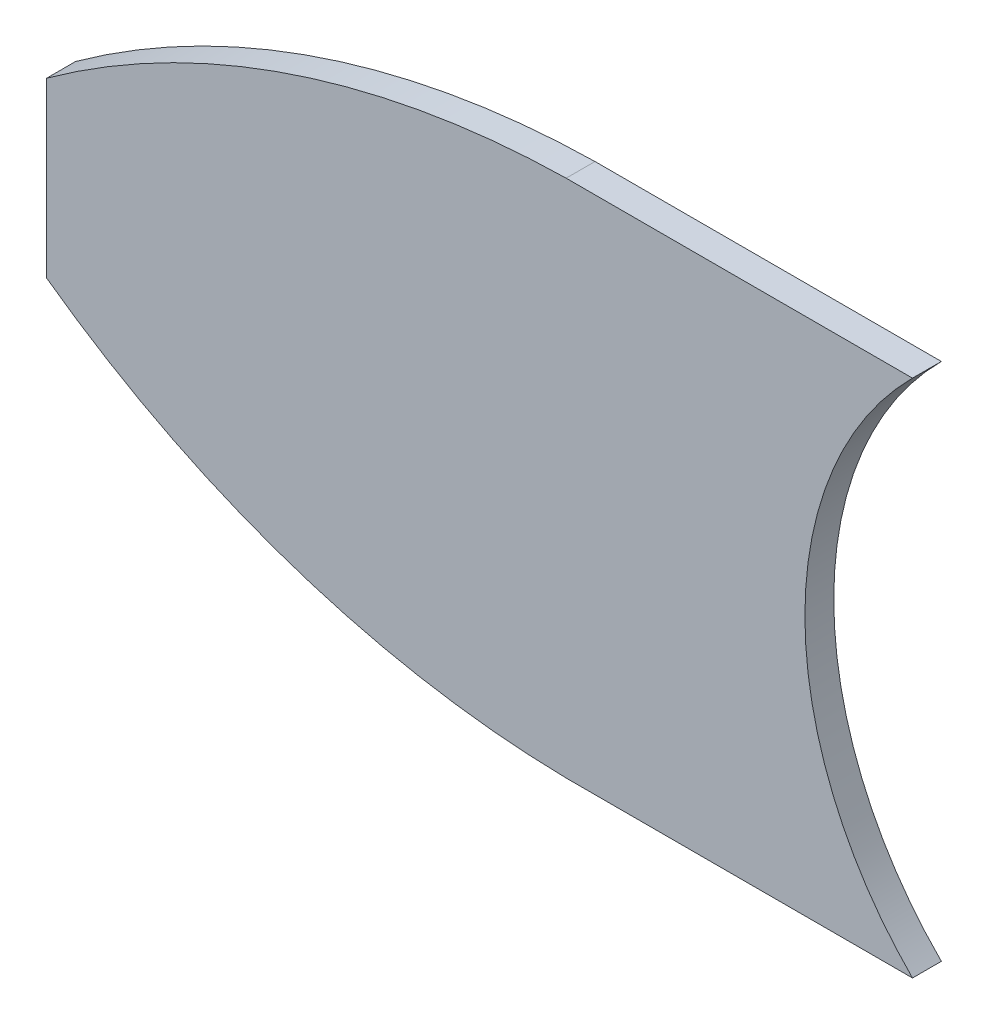
SolidWorks part; units mm, degrees
ref_plane "Front Plane" through (0, 0, 0) normal (0, 0, 1) x (1, 0, 0)
ref_plane "Top Plane" through (0, 0, 0) normal (0, 1, 0) x (1, 0, 0)
ref_plane "Right Plane" through (0, 0, 0) normal (1, 0, 0) x (0, 0, -1)
sketch "Sketch1" plane through (0, 0, 0) normal (0, 0, 1) x (1, 0, 0)
  line L0 (-300, 90) -> (6.8309, 90) construction
  line L1 (0, 0) -> (-120, 0)
  line L3 (0, 180) -> (-120, 180)
  line L4 (-300, 60) -> (-300, 120)
  arc A2 (-300, 120) -> (-120, 180) centre (-114.4729, -136.5812) cw
  arc A3 (-300, 60) -> (-120, 0) centre (-114.4729, 316.5812) ccw
  arc A4 (0, 180) -> (0, 0) centre (90, 90) ccw
  point P7 (-300, 0)
  point P10 (-300, 180)
  dimension "D3" = 316.6294
  dimension "D4" = 127.2792
  dimension "D1" = 300
  dimension "D2" = 180
  dimension "D5" = 114.4729
  dimension "D6" = 120
extrude "Boss-Extrude1" add sketch "Sketch1" along normal blind 10
